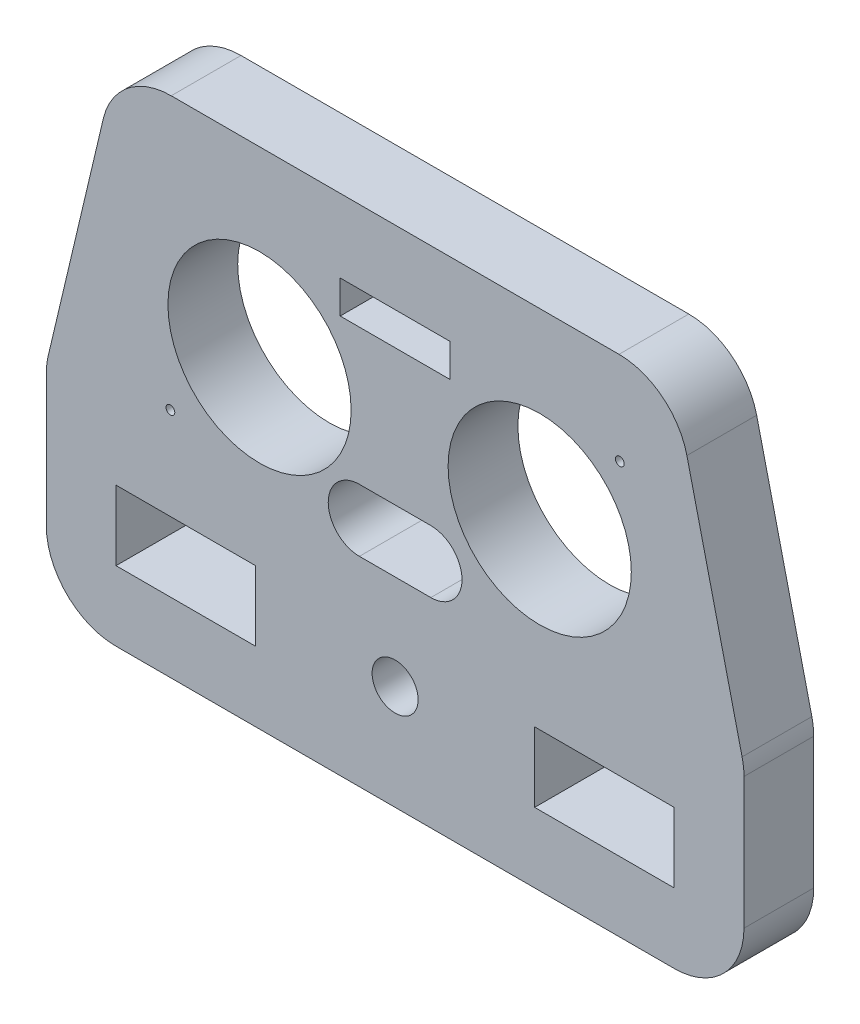
SolidWorks part; units mm, degrees
ref_plane "Front Plane" through (0, 0, 0) normal (0, 0, 1) x (1, 0, 0)
ref_plane "Top Plane" through (0, 0, 0) normal (0, 1, 0) x (1, 0, 0)
ref_plane "Right Plane" through (0, 0, 0) normal (1, 0, 0) x (0, 0, -1)
sketch "Sketch1" plane through (0, 0, 0) normal (0, 0, 1) x (1, 0, 0)
  line L1 (-31.75, -9.525) -> (31.75, -9.525)
  line L2 (-31.75, -9.525) -> (-31.75, 9.525)
  line L3 (-31.75, 9.525) -> (31.75, 9.525)
  line L4 (31.75, -9.525) -> (31.75, 9.525)
  line L5 (-31.75, -9.525) -> (31.75, 9.525) construction
  line L6 (-31.75, 9.525) -> (31.75, -9.525) construction
  point P0 (0, 0)
  dimension "D1" = 19.05
  dimension "D2" = 63.5
extrude "Boss-Extrude1" add sketch "Sketch1" along normal blind 6.35
sketch "Sketch2" plane through (0, 0, 6.35) normal (0, 0, 1) x (1, 0, 0)
  line L0 (0, 3.175) -> (0, -3.175) construction
  line L1 (-31.75, -9.525) -> (31.75, -9.525) construction
  line L2 (-31.75, -3.175) -> (31.75, -3.175) construction
  line L3 (-31.75, 9.525) -> (-31.75, -9.525) construction
  line L4 (31.75, -9.525) -> (31.75, 9.525) construction
  line L5 (-31.75, 3.175) -> (31.75, 3.175) construction
  line L7 (-25.4, 3.175) -> (-12.7, 3.175)
  line L8 (-25.4, 3.175) -> (-25.4, -3.175)
  line L9 (-25.4, -3.175) -> (-12.7, -3.175)
  line L10 (-12.7, 3.175) -> (-12.7, -3.175)
  line L11 (12.7, 3.175) -> (25.4, 3.175)
  line L12 (12.7, 3.175) -> (12.7, -3.175)
  line L13 (12.7, -3.175) -> (25.4, -3.175)
  line L14 (25.4, 3.175) -> (25.4, -3.175)
  circle A0 centre (0, 0) radius 2.0955
  dimension "D3" = 4.191
  dimension "D1" = 6.35
  dimension "D2" = 6.35
  dimension "D4" = 12.7
  dimension "D5" = 12.7
  dimension "D6" = 12.7
  dimension "D7" = 12.7
extrude "Cut-Extrude1" cut sketch "Sketch2" against normal blind 6.35
sketch "Sketch3" plane through (0, 0, 6.35) normal (0, 0, 1) x (1, 0, 0)
  line L0 (-31.75, 9.525) -> (-25.4, 36.375)
  line L1 (-25.4, 36.375) -> (25.4, 36.375)
  line L2 (25.4, 36.375) -> (31.75, 9.525)
  line L3 (31.75, 9.525) -> (-31.75, 9.525)
  line L4 (0, 9.525) -> (0, 36.375) construction
  line L5 (22.5, 30.025) -> (-22.5, 30.025) construction
  point P11 (0, 36.375)
  dimension "D1" = 6.35
  dimension "D2" = 6.35
extrude "Boss-Extrude2" add sketch "Sketch3" against normal blind 6.35
sketch "Sketch4" plane through (0, 0, 6.35) normal (0, 0, 1) x (1, 0, 0)
  line L4 (-3.25, 8.6375) -> (3.25, 8.6375)
  line L5 (3.25, 14.3125) -> (-3.25, 14.3125)
  line L6 (-3.25, 8.6375) -> (3.25, 8.6375)
  line L7 (3.25, 14.3125) -> (-3.25, 14.3125)
  line L14 (-5, 29.7025) -> (-5, 26.7025)
  line L15 (5, 29.7025) -> (-5, 29.7025)
  line L16 (5, 26.7025) -> (5, 29.7025)
  line L17 (-5, 26.7025) -> (5, 26.7025)
  line L18 (-5, 29.7025) -> (-5, 26.7025)
  line L19 (5, 29.7025) -> (-5, 29.7025)
  line L20 (5, 26.7025) -> (5, 29.7025)
  line L21 (-5, 26.7025) -> (5, 26.7025)
  arc A4 (3.25, 8.6375) -> (3.25, 14.3125) centre (3.25, 11.475) ccw
  arc A5 (-3.25, 14.3125) -> (-3.25, 8.6375) centre (-3.25, 11.475) ccw
  arc A6 (3.25, 8.6375) -> (3.25, 14.3125) centre (3.25, 11.475) ccw
  arc A7 (-3.25, 14.3125) -> (-3.25, 8.6375) centre (-3.25, 11.475) ccw
  dimension "D1" = 1.5875
  dimension "D2" = 0
extrude "Cut-Extrude2" cut sketch "Sketch4" against normal blind 6.35
sketch "Sketch5" plane through (0, 0, 6.35) normal (0, 0, 1) x (1, 0, 0)
  circle A2 centre (-12.34, 19.775) radius 8.3369
  circle A3 centre (-12.34, 19.775) radius 8.3369
  circle A5 centre (13.16, 19.775) radius 8.3369
  circle A6 centre (13.16, 19.775) radius 8.3369
  dimension "D1" = 0.3969
  dimension "D2" = 0.3969
extrude "Cut-Extrude3" cut sketch "Sketch5" against normal blind 6.35
sketch "Sketch6" plane through (0, 0, 0) normal (0, 0, -1) x (-1, 0, 0)
  circle A0 centre (20.45, 11.575) radius 0.3969
  circle A1 centre (-20.45, 27.975) radius 0.3969
  dimension "D1" = 0.7937
extrude "Cut-Extrude4" cut sketch "Sketch6" against normal blind 6.35
fillet "Fillet1" radius 6.35 6 edges at (31.75, -9.525, 3.175) (31.75, 9.525, 3.175) (25.4, 36.375, 3.175) (-31.75, -9.525, 3.175) (-31.75, 9.525, 3.175) (-25.4, 36.375, 3.175)
